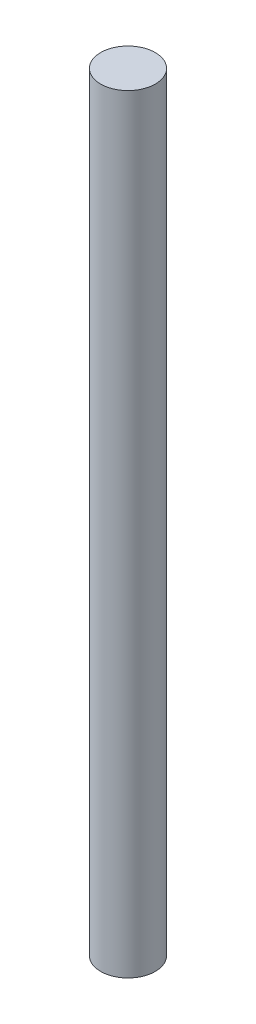
SolidWorks part; units mm, degrees
ref_plane "Front Plane" through (0, 0, 0) normal (0, 0, 1) x (1, 0, 0)
ref_plane "Top Plane" through (0, 0, 0) normal (0, 1, 0) x (1, 0, 0)
ref_plane "Right Plane" through (0, 0, 0) normal (1, 0, 0) x (0, 0, -1)
sketch "Sketch2" plane through (0, 0, 0) normal (0, 1, 0) x (1, 0, 0)
  circle A0 centre (0, 0) radius 0.5
extrude "Boss-Extrude1" add sketch "Sketch2" along normal blind 14.07
